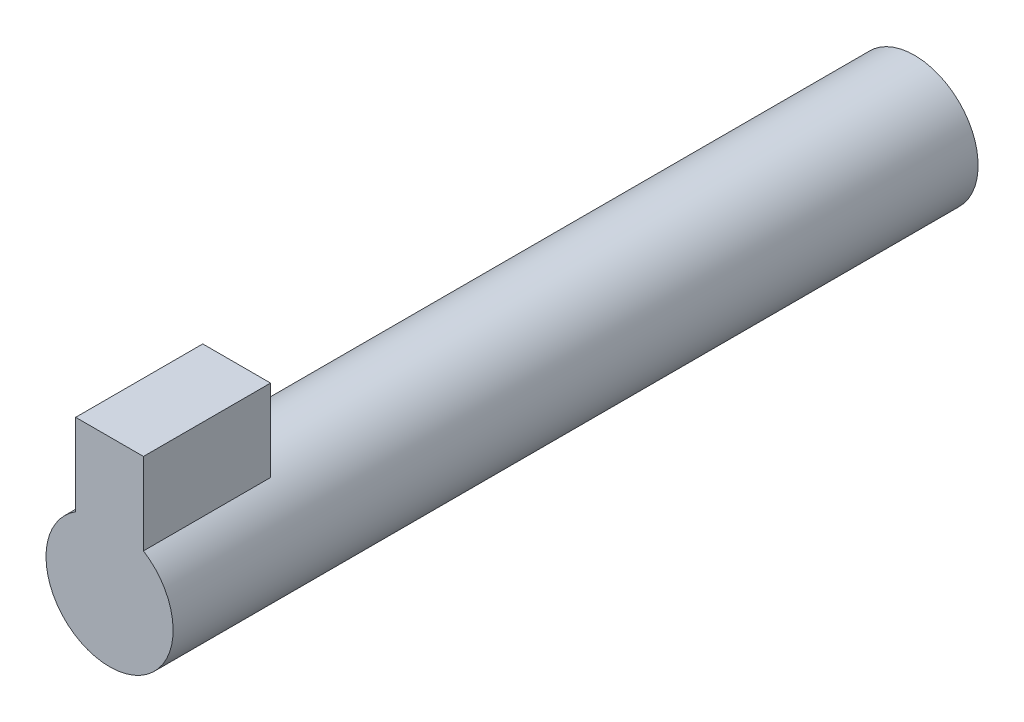
SolidWorks part; units mm, degrees
ref_plane "Front Plane" through (0, 0, 0) normal (0, 0, 1) x (1, 0, 0)
ref_plane "Top Plane" through (0, 0, 0) normal (0, 1, 0) x (1, 0, 0)
ref_plane "Right Plane" through (0, 0, 0) normal (1, 0, 0) x (0, 0, -1)
sketch "Sketch1" plane through (0, 0, 0) normal (0, 0, 1) x (1, 0, 0)
  line L1 (-2.54, 0) -> (2.54, 0)
  line L2 (-2.54, 0) -> (-2.54, 10.16)
  line L3 (-2.54, 10.16) -> (2.54, 10.16)
  line L4 (2.54, 0) -> (2.54, 10.16)
  circle A0 centre (0, 0) radius 4.7625
  dimension "D1" = 9.525
  dimension "D2" = 10.16
  dimension "D3" = 5.08
extrude "Boss-Extrude1" add sketch "Sketch1" along normal blind 9.525 contours L2 A0 L4 L1 | L4 A0 L2 L1 | A0 L4 L3 L2
sketch "Sketch2" plane through (0, 0, 0) normal (0, 0, -1) x (-1, 0, 0)
  circle A0 centre (0, 0) radius 4.7625
  dimension "D1" = 9.525
extrude "Boss-Extrude2" add sketch "Sketch2" along normal blind 50.8
